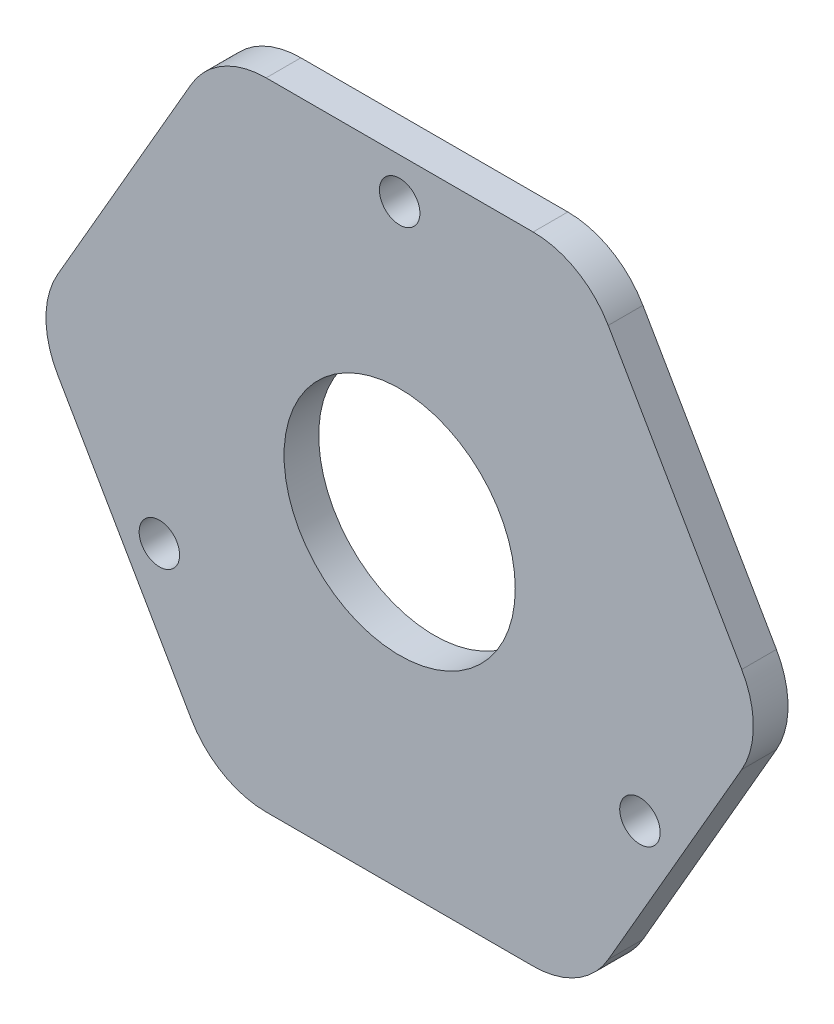
SolidWorks part; units mm, degrees
material "ПК/АБС"
ref_plane "Спереди" through (0, 0, 0) normal (0, 0, 1) x (1, 0, 0)
ref_plane "Сверху" through (0, 0, 0) normal (0, 1, 0) x (1, 0, 0)
ref_plane "Справа" through (0, 0, 0) normal (1, 0, 0) x (0, 0, -1)
sketch "Эскиз1" plane through (0, 0, 0) normal (0, 0, 1) x (1, 0, 0)
  line L0 (0, 0) -> (0, 27.5) construction
  line L1 (29.5892, 3.75) -> (18.0422, 23.75)
  line L2 (11.547, 27.5) -> (-11.547, 27.5)
  line L3 (-18.0422, 23.75) -> (-29.5892, 3.75)
  line L4 (-29.5892, -3.75) -> (-18.0422, -23.75)
  line L5 (-11.547, -27.5) -> (11.547, -27.5)
  line L6 (18.0422, -23.75) -> (29.5892, -3.75)
  circle A1 centre (0, 0) radius 27.5 construction
  circle A2 centre (0, 24) radius 1.75
  circle A3 centre (20.7846, -12) radius 1.75
  circle A4 centre (-20.7846, -12) radius 1.75
  arc A5 (-29.5892, 3.75) -> (-29.5892, -3.75) centre (-23.094, 0) ccw
  arc A6 (-18.0422, -23.75) -> (-11.547, -27.5) centre (-11.547, -20) ccw
  arc A7 (11.547, -27.5) -> (18.0422, -23.75) centre (11.547, -20) ccw
  arc A8 (29.5892, 3.75) -> (29.5892, -3.75) centre (23.094, 0) cw
  arc A9 (18.0422, 23.75) -> (11.547, 27.5) centre (11.547, 20) ccw
  arc A10 (-11.547, 27.5) -> (-18.0422, 23.75) centre (-11.547, 20) ccw
  circle A11 centre (0, 0) radius 10
  point P19 (0, 0)
  dimension "D2" = 3.5
  dimension "D4" = 7.5
  dimension "D5" = 20
  dimension "D1" = 55
  dimension "D3" = 24
extrude "Бобышка-Вытянуть1" add sketch "Эскиз1" along normal blind 3
